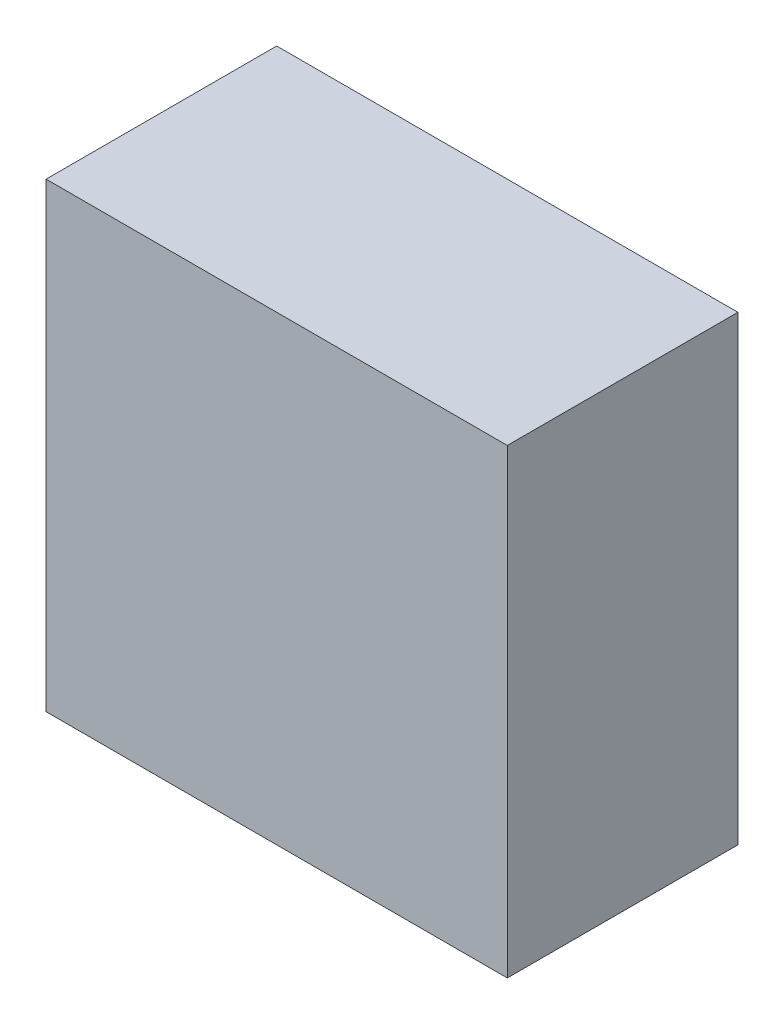
SolidWorks part; units mm, degrees
material "Perspex (TM) GS Acrylic Cast Sheet"
ref_plane "Front Plane" through (0, 0, 0) normal (0, 0, 1) x (1, 0, 0)
ref_plane "Top Plane" through (0, 0, 0) normal (0, 1, 0) x (1, 0, 0)
ref_plane "Right Plane" through (0, 0, 0) normal (1, 0, 0) x (0, 0, -1)
sketch "Sketch1" plane through (0, 0, 0) normal (0, 1, 0) x (1, 0, 0)
  line L5 (-5, -2.5) -> (5, -2.5)
  line L6 (-5, -2.5) -> (-5, 2.5)
  line L7 (-5, 2.5) -> (5, 2.5)
  line L8 (5, -2.5) -> (5, 2.5)
  line L9 (-5, -2.5) -> (5, 2.5) construction
  line L10 (-5, 2.5) -> (5, -2.5) construction
  point P0 (0, 0)
  dimension "D1" = 10
  dimension "D2" = 5
extrude "Boss-Extrude1" add sketch "Sketch1" along normal blind 10
